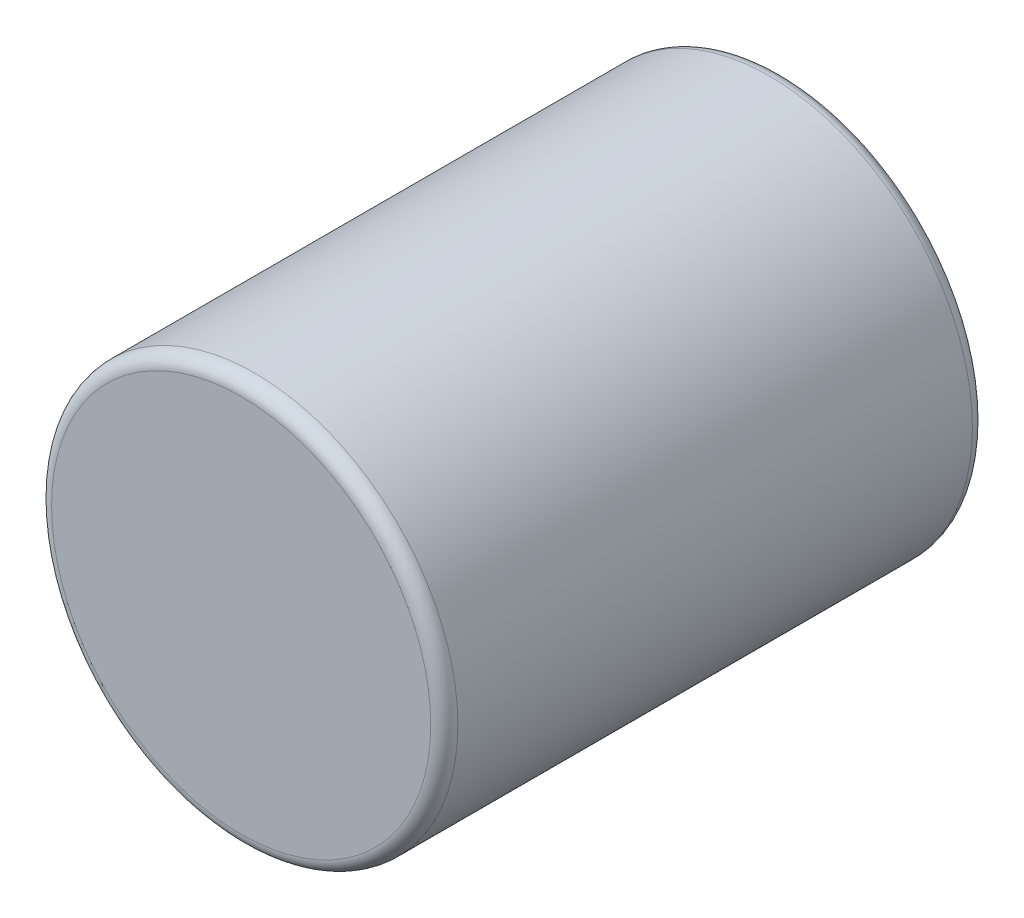
SolidWorks part; units mm, degrees
material "AISI 1020 钢，冷轧"
ref_plane "前视基准面" through (0, 0, 0) normal (0, 0, 1) x (1, 0, 0)
ref_plane "上视基准面" through (0, 0, 0) normal (0, 1, 0) x (1, 0, 0)
ref_plane "右视基准面" through (0, 0, 0) normal (1, 0, 0) x (0, 0, -1)
sketch "草图1" plane through (0, 0, 0) normal (0, 0, 1) x (1, 0, 0)
  circle A0 centre (0, 0) radius 1.5
  dimension "D1" = 3
extrude "凸台-拉伸1" add sketch "草图1" along normal blind 4
fillet "圆角1" radius 0.1 2 edges at (1.5, 0, 4) (1.5, 0, 0)
